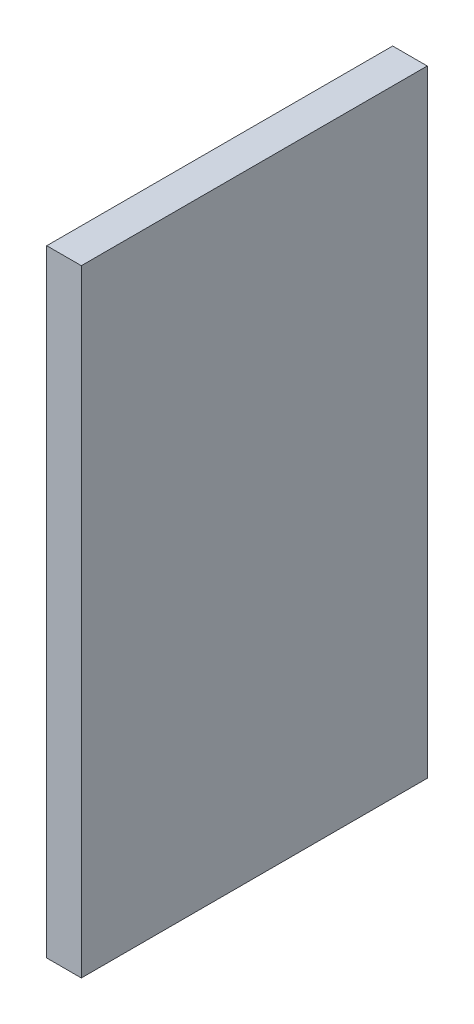
SolidWorks part; units mm, degrees
ref_plane "Front Plane" through (0, 0, 0) normal (0, 0, 1) x (1, 0, 0)
ref_plane "Top Plane" through (0, 0, 0) normal (0, 1, 0) x (1, 0, 0)
ref_plane "Right Plane" through (0, 0, 0) normal (1, 0, 0) x (0, 0, -1)
sketch "Sketch1" plane through (0, 0, 0) normal (0, 0, 1) x (1, 0, 0)
  line L1 (-3, 53.5) -> (3, 53.5)
  line L2 (-3, 53.5) -> (-3, -53.5)
  line L3 (-3, -53.5) -> (3, -53.5)
  line L4 (3, 53.5) -> (3, -53.5)
  line L5 (-3, 53.5) -> (3, -53.5) construction
  line L6 (-3, -53.5) -> (3, 53.5) construction
  point P0 (0, 0)
  dimension "D1" = 6
  dimension "D2" = 107
extrude "Boss-Extrude1" add sketch "Sketch1" along normal blind 60
